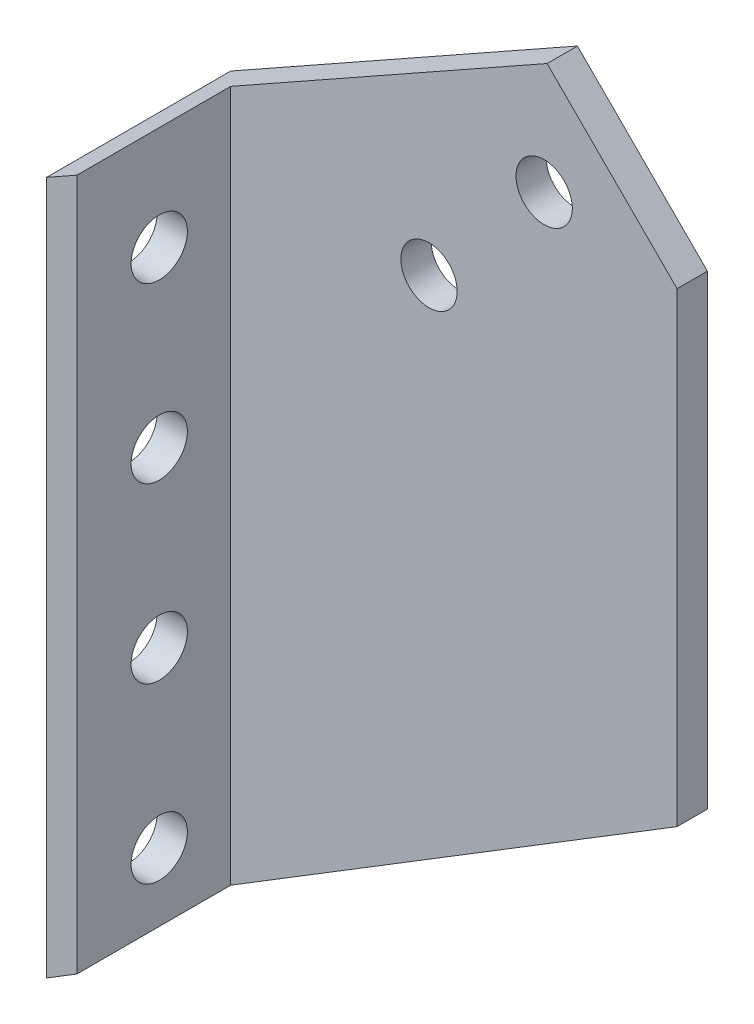
SolidWorks part; units mm, degrees
ref_plane "前视基准面" through (0, 0, 0) normal (0, 0, 1) x (1, 0, 0)
ref_plane "上视基准面" through (0, 0, 0) normal (0, 1, 0) x (1, 0, 0)
ref_plane "右视基准面" through (0, 0, 0) normal (1, 0, 0) x (0, 0, -1)
sketch "草图1" plane through (0, 0, 0) normal (0, 0, 1) x (1, 0, 0)
  line L0 (-1074.6542, -63.3767) -> (48925.3458, -63.3767) construction
  line L1 (-159.1564, -1011.9129) -> (-159.1564, 48988.0871) construction
  line L2 (-119.6564, -63.3767) -> (-119.6564, 256.6233)
  line L3 (-1159.1564, 71.6233) -> (48840.8436, 71.6233) construction
  line L4 (100.3436, 71.6233) -> (100.3436, 286.6233)
  line L5 (40.3436, -1032.1436) -> (40.3436, 48967.8564) construction
  line L6 (-1249.4209, 346.6233) -> (48750.5791, 346.6233) construction
  line L7 (-119.6564, -63.3767) -> (100.3436, 71.6233)
  line L8 (100.3436, 286.6233) -> (40.3436, 346.6233)
  line L9 (40.3436, 346.6233) -> (-119.6564, 256.6233)
  line L10 (1840.8436, -949.9726) -> (1840.8436, 49050.0274) construction
  line L11 (-67.2456, 2321.6233) -> (49932.7544, 2321.6233) construction
  line L12 (1840.8436, 2321.6233) -> (-31377.3484, -35048.8426) construction
  circle A0 centre (-14.1564, 234.7483) radius 13
  circle A1 centre (38.9927, 294.5411) radius 13
  point P21 (-159.1564, 71.6233)
  point P22 (-14.1564, 234.7483)
  point P23 (38.9927, 294.5411)
  dimension "D13" = 26
  dimension "D1" = 320
  dimension "D2" = 39.5
  dimension "D3" = 135
  dimension "D4" = 215
  dimension "D5" = 160
  dimension "D6" = 60
  dimension "D7" = 60
  dimension "D8" = 2000
  dimension "D9" = 2250
  dimension "D10" = 80
  dimension "D11" = 145
extrude "凸台-拉伸1" add sketch "草图1" along normal blind 14
sketch "草图3" plane through (0, 0, 14) normal (0, 0, 1) x (1, 0, 0)
  line L0 (-105.6564, 264.4983) -> (-105.6564, -54.7858)
  line L1 (40.3436, 346.6233) -> (-119.6564, 256.6233) construction
  line L2 (-119.6564, -63.3767) -> (100.3436, 71.6233) construction
  line L3 (-119.6564, 256.6233) -> (-119.6564, -63.3767) construction
  line L9 (-119.6564, -63.3767) -> (100.3436, 71.6233)
  line L10 (100.3436, 71.6233) -> (100.3436, 286.6233)
  line L11 (100.3436, 286.6233) -> (40.3436, 346.6233)
  line L12 (40.3436, 346.6233) -> (-119.6564, 256.6233)
  line L13 (-119.6564, 256.6233) -> (-119.6564, -63.3767)
  line L14 (-119.6564, -63.3767) -> (-105.6564, -54.7858)
  line L17 (-105.6564, 264.4983) -> (-119.6564, 256.6233)
  line L18 (-119.6564, 256.6233) -> (-119.6564, -63.3767)
  dimension "D1" = 14
  dimension "D2" = 0
extrude "凸台-拉伸2" add sketch "草图3" along normal blind 71
sketch "草图5" plane through (-119.6564, 0, 0) normal (-1, 0, 0) x (0, 0, 1)
  line L0 (47, 256.6233) -> (47, -63.3767) construction
  line L1 (85, 256.6233) -> (0, 256.6233) construction
  line L2 (85, -63.3767) -> (0, -63.3767) construction
  line L3 (85, 256.6233) -> (85, -63.3767) construction
  line L4 (0, 216.6233) -> (85, 216.6233) construction
  line L5 (0, 256.6233) -> (0, -63.3767) construction
  circle A0 centre (47, 216.6233) radius 13
  point P12 (47, 216.6233)
  dimension "D1" = 38
  dimension "D2" = 40
extrude "切除-拉伸3" cut sketch "草图5" against normal through all
pattern_linear "阵列(线性)1" count 4 spacing 80 along (0, -1, 0) of "切除-拉伸3"
